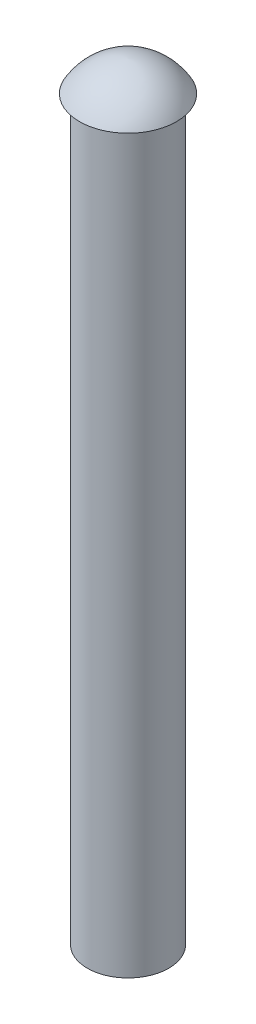
SolidWorks part; units mm, degrees
ref_plane "Front Plane" through (0, 0, 0) normal (0, 0, 1) x (1, 0, 0)
ref_plane "Top Plane" through (0, 0, 0) normal (0, 1, 0) x (1, 0, 0)
ref_plane "Right Plane" through (0, 0, 0) normal (1, 0, 0) x (0, 0, -1)
sketch "Sketch2" plane through (0, 0, 0) normal (0, 0, 1) x (1, 0, 0)
  line L0 (0, 29.0992) -> (0, -29.0992) construction
  line L1 (0, -45.1212) -> (3.6195, -45.1212)
  line L2 (3.6195, -45.1212) -> (3.6195, 20.4108)
  line L3 (3.6195, 20.4108) -> (4.318, 20.4108)
  line L4 (0, -45.1212) -> (0, 23.0783)
  arc A0 (4.318, 20.4108) -> (0, 23.0783) centre (-0.2803, 17.7959) ccw
  dimension "D1" = 3.6195
  dimension "D2" = 0.6985
  dimension "D3" = 65.532
revolve "Revolve1" add sketch "Sketch2" angle 360 about L4
